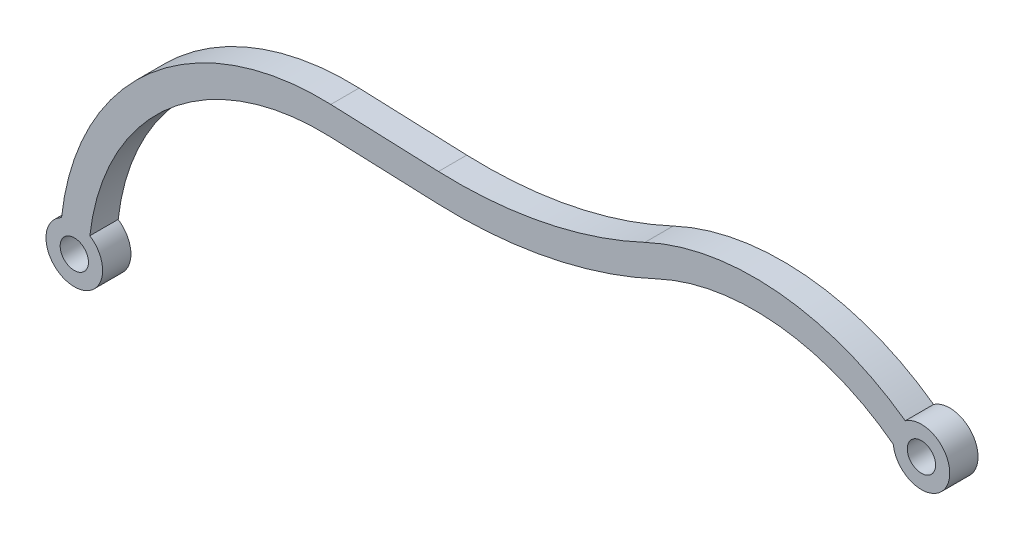
SolidWorks part; units mm, degrees
ref_plane "Спереди" through (0, 0, 0) normal (0, 0, 1) x (1, 0, 0)
ref_plane "Сверху" through (0, 0, 0) normal (0, 1, 0) x (1, 0, 0)
ref_plane "Справа" through (0, 0, 0) normal (1, 0, 0) x (0, 0, -1)
other "Configuration Table"
sketch "Sketch1" plane through (0, 0, 0) normal (0, 0, 1) x (1, 0, 0)
  line L1 (-79.641, 9.4879) -> (-68.2312, 9.042)
  line L2 (-66.206, 12.3668) -> (-75.6987, 12.7378) construction
  line L3 (-79.6996, 7.989) -> (-68.2898, 7.5431)
  line L4 (-79.5824, 10.9867) -> (-68.1726, 10.5408)
  circle A0 centre (-17, 9.9282) radius 3
  circle A1 centre (-17, 9.9282) radius 1.5
  circle A3 centre (-106.7589, -16.339) radius 3
  circle A4 centre (-106.7589, -16.339) radius 1.5
  arc A6 (-106.6773, -14.4171) -> (-79.641, 9.4879) centre (-80.6606, -16.6004) cw
  arc A7 (-68.2312, 9.042) -> (-45.6614, 13.6144) centre (-66.3314, 57.6536) ccw
  arc A8 (-45.6614, 13.6144) -> (-18.7578, 10.5494) centre (-34.6965, -9.7473) cw
  arc A9 (-105.1825, -14.5425) -> (-79.6996, 7.989) centre (-80.6606, -16.6004) cw
  arc A10 (-68.2898, 7.5431) -> (-45.0241, 12.2565) centre (-66.3314, 57.6536) ccw
  arc A11 (-45.0241, 12.2565) -> (-19.8113, 9.4688) centre (-34.6965, -9.7473) cw
  arc A12 (-108.172, -14.2916) -> (-79.5824, 10.9867) centre (-80.6606, -16.6004) cw
  arc A13 (-68.1726, 10.5408) -> (-46.2987, 14.9723) centre (-66.3314, 57.6536) ccw
  arc A14 (-46.2987, 14.9723) -> (-17.9742, 11.8405) centre (-34.6965, -9.7473) cw
  arc A15 (-45.6614, 13.6144) -> (-18.8928, 10.6546) centre (-34.6965, -9.7473) cw construction
  dimension "D1" = 6
  dimension "D2" = 3
  dimension "D3" = 6
  dimension "D4" = 3
  dimension "D5" = 1.5
  dimension "D6" = 1.5
extrude "Boss-Extrude1" add sketch "Sketch1" along normal blind 3
